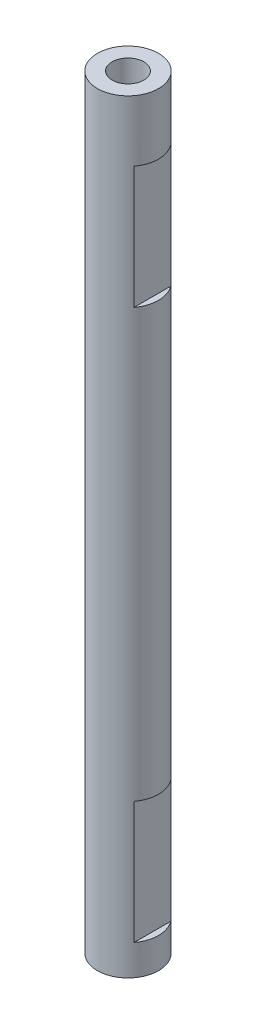
SolidWorks part; units mm, degrees
ref_plane "正面" through (0, 0, 0) normal (0, 0, 1) x (1, 0, 0)
ref_plane "平面" through (0, 0, 0) normal (0, 1, 0) x (1, 0, 0)
ref_plane "右側面" through (0, 0, 0) normal (1, 0, 0) x (0, 0, -1)
sketch "ｽｹｯﾁ1" plane through (0, 0, 0) normal (0, 1, 0) x (1, 0, 0)
  circle A0 centre (0, 0) radius 5
  dimension "D1" = 10
extrude "ﾎﾞｽ - 押し出し1" add sketch "ｽｹｯﾁ1" along normal blind 125
sketch "ｽｹｯﾁ2" plane through (0, 125, 0) normal (0, 1, 0) x (1, 0, 0)
  circle A0 centre (0, 0) radius 2.5
  dimension "D1" = 5
hole_wizard "M5x0.8 下側ねじ穴" positions "3Dｽｹｯﾁ1" profile "ｽｹｯﾁ3" hole size "M5" standard "JIS"
sketch3d "3Dｽｹｯﾁ1"
  point P0 (0, 125, 0)
sketch "ｽｹｯﾁ3" plane through (0, 125, 0) normal (1, 0, 0) x (0, 0, 1)
  line L0 (0, 0) -> (0, 17.5622)
  line L1 (0, 17.5622) -> (2.6, 16)
  line L2 (2.6, 16) -> (2.6, 0)
  line L5 (2.6, 0) -> (0, 0)
  line L10 (0, 17.5622) -> (-2.6, 16) construction
  line L11 (0, -6.35) -> (0, 107.95) construction
  dimension "穴の直径" = 5.2
  dimension "穴の深さ" = 16
  dimension "ﾄﾞﾘﾙ角度" = 118
sketch "ｽｹｯﾁ4" plane through (0, 0, 0) normal (0, -1, 0) x (1, 0, 0)
  circle A0 centre (0, 0) radius 3
  dimension "D1" = 6
hole_wizard "M5x0.8 上側ねじ穴" positions "3Dｽｹｯﾁ2" profile "ｽｹｯﾁ5" hole size "M5" standard "JIS"
sketch3d "3Dｽｹｯﾁ2"
  point P0 (0, 0, 0)
  point P3 (0, 0, 0)
sketch "ｽｹｯﾁ5" plane through (0, 0, 0) normal (1, 0, 0) x (0, 0, -1)
  line L0 (0, 0) -> (0, 17.5622)
  line L1 (0, 17.5622) -> (2.6, 16)
  line L2 (2.6, 16) -> (2.6, 0)
  line L5 (2.6, 0) -> (0, 0)
  line L10 (0, 17.5622) -> (-2.6, 16) construction
  line L11 (0, -6.35) -> (0, 107.95) construction
  dimension "穴の直径" = 5.2
  dimension "穴の深さ" = 16
  dimension "ﾄﾞﾘﾙ角度" = 118
ref_plane "平面1" through (0, 62.5, 0) normal (0, -1, 0) x (-1, 0, 0)
ref_plane "平面2" through (0, 115, 0) normal (0, 1, 0) x (1, 0, 0)
sketch "ｽｹｯﾁ8" plane through (0, 115, 0) normal (0, 1, 0) x (1, 0, 0)
  line L0 (0, 0) -> (-5, 0) construction
  line L1 (4, -3) -> (4, 3)
  line L4 (-4, 3) -> (-4, -3)
  line L8 (0.5981, 4.9641) -> (-3.732, 2.4641) [skipped]
  line L9 (4.5981, 1.9641) -> (0.268, 4.4641) [skipped]
  line L10 (-4, -2.3094) -> (0.3301, -4.8094) [skipped]
  line L11 (0, -4.6188) -> (4.3301, -2.1188) [skipped]
  arc A0 (-4, 3) -> (-4, -3) centre (0, 0) ccw
  circle A1 centre (0, 0) radius 5 construction
  arc A2 (4, 3) -> (4, -3) centre (0, 0) cw
  dimension "D1" = 8
extrude "ｶｯﾄ - 押し出し5" cut sketch "ｽｹｯﾁ8" against normal blind 20 contours A2 L1 | L0 L4 A0 | L4 L0 A0
ref_plane "平面3" through (0, 5, 0) normal (0, -1, 0) x (-1, 0, 0)
sketch "ｽｹｯﾁ9" plane through (0, 5, 0) normal (0, -1, 0) x (-1, 0, 0)
  line L0 (-5, 0) -> (5, 0) construction
  line L2 (-4, 3) -> (-4, -3)
  line L5 (4, -3) -> (4, 3)
  line L8 (0.5814, 4.9545) -> (-3.7487, 2.4545) [skipped]
  line L9 (4.5814, 1.9737) -> (0.2513, 4.4737) [skipped]
  line L10 (0, -4.6188) -> (4.3301, -2.1188) [skipped]
  line L11 (-4, -2.3094) -> (0.3301, -4.8094) [skipped]
  arc A0 (-4, 3) -> (-4, -3) centre (0, 0) ccw
  circle A1 centre (0, 0) radius 5 construction
  arc A2 (4, 3) -> (4, -3) centre (0, 0) cw
  dimension "D1" = 8
extrude "ｶｯﾄ - 押し出し6" cut sketch "ｽｹｯﾁ9" against normal blind 20 contours A0 L0 L2 | L0 A0 L2 | L5 L0 A2 | L0 L5 A2
